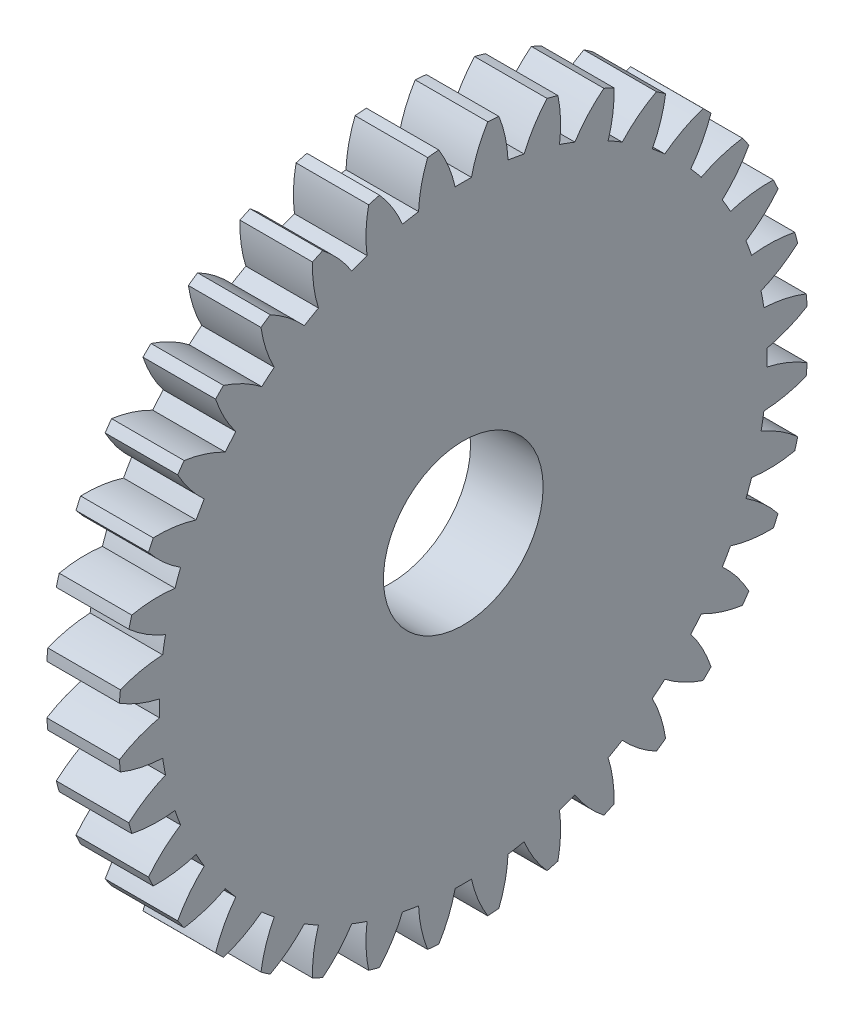
SolidWorks part; units mm, degrees
ref_plane "Plane1" through (0, 0, 0) normal (0, 0, 1) x (1, 0, 0)
ref_plane "Plane2" through (0, 0, 0) normal (0, 1, 0) x (1, 0, 0)
ref_plane "Plane3" through (0, 0, 0) normal (1, 0, 0) x (0, 0, -1)
sketch "HoldingSke" plane through (0, 0, 0) normal (0, 1, 0) x (1, 0, 0)
  line L0 (0, 0) -> (0.3236, -0.2351)
  line L1 (-15, 0) -> (100, 0) construction
  line L2 (0, 0) -> (-2.1039, 2.3779)
  line L3 (0, 0) -> (-11.863, 4.5341)
  line L4 (0, 0) -> (6.9867, 5.0761)
  line L5 (0, 0) -> (-46.8476, -17.4728)
  line L6 (0, 0) -> (-8.2896, -5.593)
  line L7 (-2.1039, 2.3779) -> (8.6586, 51.2059)
  line L8 (-76.2, 54.61) -> (-74.8, 54.61)
  line L9 (-71.009, 38.7566) -> (-53.1078, 45.2721)
  line L10 (-76.2, 71.12) -> (104.1128, 71.12)
  line L11 (0, 0) -> (-10, 0)
  line L12 (-76.2, 101.6) -> (-76.113, 101.6)
  line L13 (24.9733, 27.94) -> (52.9518, 28.4284)
  line L14 (24.9733, 27.94) -> (24.9743, 27.94)
  line L15 (24.9733, 27.94) -> (100.4006, 29.5858)
  line L16 (-63.627, -2.5) -> (-12.827, -2.5)
  circle A0 centre (0, 0) radius 4
  circle A1 centre (0, 0) radius 37.5
  circle A2 centre (0, 0) radius 37.5
  circle A3 centre (0, 0) radius 4
  dimension "MHD" = 75
  dimension "Hub_dia" = 75
  dimension "Bore" = 8
  dimension "MBD" = 8
  dimension "Num_teeth" = 36
  dimension "Pitch" = 0.4
  dimension "Overall_len" = 50
  dimension "Show_teeth" = 36
  dimension "Thickness" = 10
  dimension "OAL" = 50.0001
  dimension "T_dim" = 1.4
  dimension "Ap" = 20
  dimension "H" = 19.05
  dimension "Pitch_radius" = 180.3128
  dimension "Width" = 10
  dimension "Backlash" = 0.087
  dimension "Addendum_fac" = 1
  dimension "Dedendum_fac" = 1.25
  dimension "Clearance_fac" = 0.25
  dimension "Dedendum_add" = 0.001
  dimension "Module" = 2.5
sketch "BasProSke" plane through (0, 0, 0) normal (0, 1, 0) x (1, 0, 0)
  line L0 (-10, 0) -> (60, 0) construction
  line L1 (0, 0) -> (0, 47.5)
  line L2 (0, 0) -> (10, 0)
  line L3 (10, 0) -> (10, 47.5)
  line L4 (10, 47.5) -> (0, 47.5)
  dimension "Thickness" = 10
  dimension "Diameter" = 95
revolve "Base-Revolve" add sketch "BasProSke" angle 360 about L0
sketch "TooCutSke" plane through (0, 0, 0) normal (1, 0, 0) x (0, 0, -1)
  line L1 (0, 0) -> (0, 107) construction
  line L2 (0, 0) -> (-2.1151, 44.9503) construction
  line L3 (0, 0) -> (-7.8377, 89.5849) construction
  line L4 (-2.1151, 44.9503) -> (-3.9188, 44.7925) construction
  arc A0 (1.124, 41.8589) -> (-1.124, 41.8589) centre (0, 0) ccw
  arc A1 (3.3848, 47.4047) -> (-3.3848, 47.4047) centre (0, 0) ccw
  circle A2 centre (0, 0) radius 45 construction
  circle A3 centre (0, 0) radius 42.2862 construction
  arc A4 (-1.124, 41.8589) -> (-3.3848, 47.4047) centre (-18.6903, 37.9314) ccw
  arc A5 (3.3848, 47.4047) -> (1.124, 41.8589) centre (18.6903, 37.9314) ccw
  dimension "Root_dia" = 83.748
  dimension "Overcut_dia" = 95.0508
  dimension "Pitch_dia" = 90
  dimension "Base_dia" = 84.5723
  dimension "Flank_rad" = 18
  dimension "Half_ang" = 5
  dimension "Half_CT" = 1.8106
extrude "ToothCut" cut sketch "TooCutSke" along normal through all
fillet "Breaks" [suppressed] radius 0.05
fillet "RootFillets" [suppressed] radius 0.626
pattern_circular "TeethCuts" count 36 every 10 about axis through (-10, 0, 0) along (1, 0, 0) of "ToothCut", "RootFillets", "Breaks"
sketch "HubNeaOneSke" plane through (0, 0, 0) normal (-1, 0, 0) x (0, 0, 1)
  circle A0 centre (0, 0) radius 37.5
  dimension "Diameter" = 75
extrude "HubNearOne" [suppressed] add sketch "HubNeaOneSke" along normal blind 40.0001
sketch "HubNeaBotSke" plane through (0, 0, 0) normal (-1, 0, 0) x (0, 0, 1)
  circle A0 centre (0, 0) radius 37.5
  dimension "Diameter" = 75
extrude "HubNearBoth" [suppressed] add sketch "HubNeaBotSke" along normal blind 20
ref_plane "FarPln" through (10, 0, 0) normal (1, 0, 0) x (0, 0, -1)
sketch "HubFarSke" plane through (10, 0, 0) normal (1, 0, 0) x (0, 0, -1)
  circle A0 centre (0, 0) radius 37.5
  dimension "Diameter" = 75
extrude "HubFar" [suppressed] add sketch "HubFarSke" along normal blind 20
sketch "BorSke" plane through (0, 0, 0) normal (1, 0, 0) x (0, 0, -1)
  circle A0 centre (0, 0) radius 4
  dimension "Diameter" = 8
extrude "Bore" cut sketch "BorSke" along normal mid plane 100.0001
sketch "KeySke" plane through (0, 0, 0) normal (1, 0, 0) x (0, 0, -1)
  line L0 (-1.5, 0) -> (-1.5, 5.4)
  line L1 (-1.5, 5.4) -> (1.5, 5.4)
  line L2 (1.5, 5.4) -> (1.5, 0)
  line L3 (0, 0) -> (0, 34) construction
  line L4 (-1.5, 0) -> (1.5, 0)
  dimension "Offset" = 5.4
  dimension "Width" = 3
extrude "Keyway" [suppressed] cut sketch "KeySke" along normal mid plane 100.0001
pattern_circular "Keyway2" [suppressed] count 2 every 90 about axis through (-10, 0, 0) along (1, 0, 0)
sketch "草圖1" plane through (10, 0, 0) normal (1, 0, 0) x (0, 0, -1)
  circle A0 centre (0, 0) radius 11
  dimension "D1" = 22
extrude "除料-伸長1" cut sketch "草圖1" against normal blind 10
equation "' \"Module@HoldingSke\" = 6.35"
equation "' \"Num_teeth@HoldingSke\" = 12"
equation "' \"Ap@HoldingSke\" =  20"
equation "' \"Ap@HoldingSke\" = 20"
equation "' \"Width@HoldingSke\" = 0.5 * 25.4"
equation "' \"Hub_dia@HoldingSke\"= 1 * 25.4"
equation "' \"Hub_dia@HoldingSke\" = 1 * 25.4"
equation "' \"Overall_len@HoldingSke\" = 1.0 * 25.4"
equation "' \"Bore@HoldingSke\" = 0.75 * 25.4"
equation "' \"T_dim@HoldingSke\" = 0.1 * 25.4"
equation "' \"Width@KeySke\" = 0.25 * 25.4"
equation "' \"Show_teeth@HoldingSke\" = 13"
equation "' \"Backlash@HoldingSke\" = 0.009 * 25.4"
equation "' \"Addendum_fac@HoldingSke\" = 1.0"
equation "' \"Dedendum_fac@HoldingSke\" = 1.25"
equation "' \"Dedendum_add@HoldingSke\" = 0.00005 * 25.4"
equation "' \"Clearance_fac@HoldingSke\" = 0.25"
equation "\"Pitch@HoldingSke\" = 1 / \"Module@HoldingSke\""
equation "\"Overcut_dia@TooCutSke\" = (\"Num_teeth@HoldingSke\" + 2 * \"Addendum_fac@HoldingSke\") / \"Pitch@HoldingSke\" + 0.002 * 25.4"
equation "\"Pitch_dia@TooCutSke\" = \"Num_teeth@HoldingSke\" / \"Pitch@HoldingSke\""
equation "\"Base_dia@TooCutSke\" = \"Num_teeth@HoldingSke\" / \"Pitch@HoldingSke\" * cos((\"Ap@HoldingSke\"  * 3.14159265 / 180))"
equation "\"Root_dia@TooCutSke\" = (\"Num_teeth@HoldingSke\" + 2) / \"Pitch@HoldingSke\" - 2 * (\"Addendum_fac@HoldingSke\" + \"Dedendum_fac@HoldingSke\") / \"Pitch@HoldingSke\" - \"Dedendum_add@HoldingSke\" * 2"
equation "\"Half_ang@TooCutSke\" = 180 / \"Num_teeth@HoldingSke\""
equation "\"Half_CT@TooCutSke\" = \"Num_teeth@HoldingSke\" / \"Pitch@HoldingSke\" * sin((3.14159265 / 2 / \"Num_teeth@HoldingSke\")) / 2 - 7 * \"Backlash@HoldingSke\" / 4"
equation "\"Flank_rad@TooCutSke\" = \"Num_teeth@HoldingSke\" / \"Pitch@HoldingSke\" / 5"
equation "\"Radius@RootFillets\" = \"Clearance_fac@HoldingSke\" / \"Pitch@HoldingSke\" + \"Dedendum_add@HoldingSke\""
equation "\"Break_rad@Breaks\" = 0.02 / \"Pitch@HoldingSke\""
equation "\"Thickness@HoldingSke\" = \"Width@HoldingSke\""
equation "\"OAL@HoldingSke\" = \"Thickness@HoldingSke\""
equation "\"MHD@HoldingSke\" = (\"Num_teeth@HoldingSke\" + 2) / \"Pitch@HoldingSke\" - 2 * (\"Addendum_fac@HoldingSke\" + \"Dedendum_fac@HoldingSke\")  / \"Pitch@HoldingSke\" - \"Dedendum_add@HoldingSke\" * 2"
equation "\"MBD@HoldingSke\" = (\"Num_teeth@HoldingSke\" + 2) / \"Pitch@HoldingSke\" - 2 * (\"Addendum_fac@HoldingSke\" + \"Dedendum_fac@HoldingSke\")  / \"Pitch@HoldingSke\" - \"Dedendum_add@HoldingSke\" * 2 - 0.002 * 25.4"
equation "\"MHD@HoldingSke\" = ((sgn( \"MHD@HoldingSke\" - \"Hub_dia@HoldingSke\" )-1)*( \"MHD@HoldingSke\" - \"Hub_dia@HoldingSke\" ))/-2+ \"Hub_dia@HoldingSke\""
equation "\"MBD@HoldingSke\" = ((sgn( \"MBD@HoldingSke\" - \"Bore@HoldingSke\" )-1)*( \"MBD@HoldingSke\" - \"Bore@HoldingSke\" ))/-2+ \"Bore@HoldingSke\""
equation "\"OAL@HoldingSke\" = ((sgn( \"OAL@HoldingSke\" - \"Overall_len@HoldingSke\" )+1)*( \"OAL@HoldingSke\" - \"Overall_len@HoldingSke\" ))/2 + \"Overall_len@HoldingSke\" + 0.000002 * 25.4"
equation "\"Num_teeth@TeethCuts\" = int( \"Show_teeth@HoldingSke\" ) + 1"
equation "\"Num_teeth@TeethCuts\" = ((sgn( \"Num_teeth@TeethCuts\" - \"Num_teeth@HoldingSke\" )-1)*( \"Num_teeth@TeethCuts\" - \"Num_teeth@HoldingSke\" ))/-2+ \"Num_teeth@HoldingSke\""
equation "\"Num_teeth@TeethCuts\" = ((sgn( \"Num_teeth@TeethCuts\" - 2.0)+1)*( \"Num_teeth@TeethCuts\" - 2.0))/2 +2.0"
equation "\"Angle@TeethCuts\" = 360.0 / \"Num_teeth@HoldingSke\""
equation "\"Diameter@BasProSke\" = (\"Num_teeth@HoldingSke\" + 2 * \"Addendum_fac@HoldingSke\") / \"Pitch@HoldingSke\""
equation "\"Thickness@BasProSke\"  = \"Thickness@HoldingSke\""
equation "' \"Fillet_rad@BasProSke\" =  \"Thickness@HoldingSke\" * 0.05"
equation "' \"Fillet_rad@BasProSke\" = \"Thickness@HoldingSke\" * 0.05"
equation "\"MHD@HoldingSke\" = ((sgn( \"MHD@HoldingSke\" - \"Root_dia@TooCutSke\" )-1)*( \"MHD@HoldingSke\" - \"Root_dia@TooCutSke\" ))/-2+ \"Root_dia@TooCutSke\""
equation "\"Diameter@HubNeaOneSke\" = \"MHD@HoldingSke\""
equation "\"Length@HubNearOne\" = \"OAL@HoldingSke\" - \"Thickness@BasProSke\""
equation "\"Diameter@HubNeaBotSke\" = \"MHD@HoldingSke\""
equation "\"Length@HubNearBoth\" = ( \"OAL@HoldingSke\" - \"Thickness@BasProSke\" ) / 2.0"
equation "\"Thickness@FarPln\" = \"Thickness@BasProSke\""
equation "\"Diameter@HubFarSke\" = \"MHD@HoldingSke\""
equation "\"Length@HubFar\" = ( \"OAL@HoldingSke\" - \"Thickness@BasProSke\" ) / 2.0"
equation "\"Diameter@BorSke\" = \"MBD@HoldingSke\""
equation "\"D1@Bore\" = \"OAL@HoldingSke\" * 2.0"
equation "\"D1@Keyway\" = \"OAL@HoldingSke\" * 2.0"
equation "\"Offset@KeySke\" = \"T_dim@HoldingSke\" + \"MBD@HoldingSke\" / 2.0"
